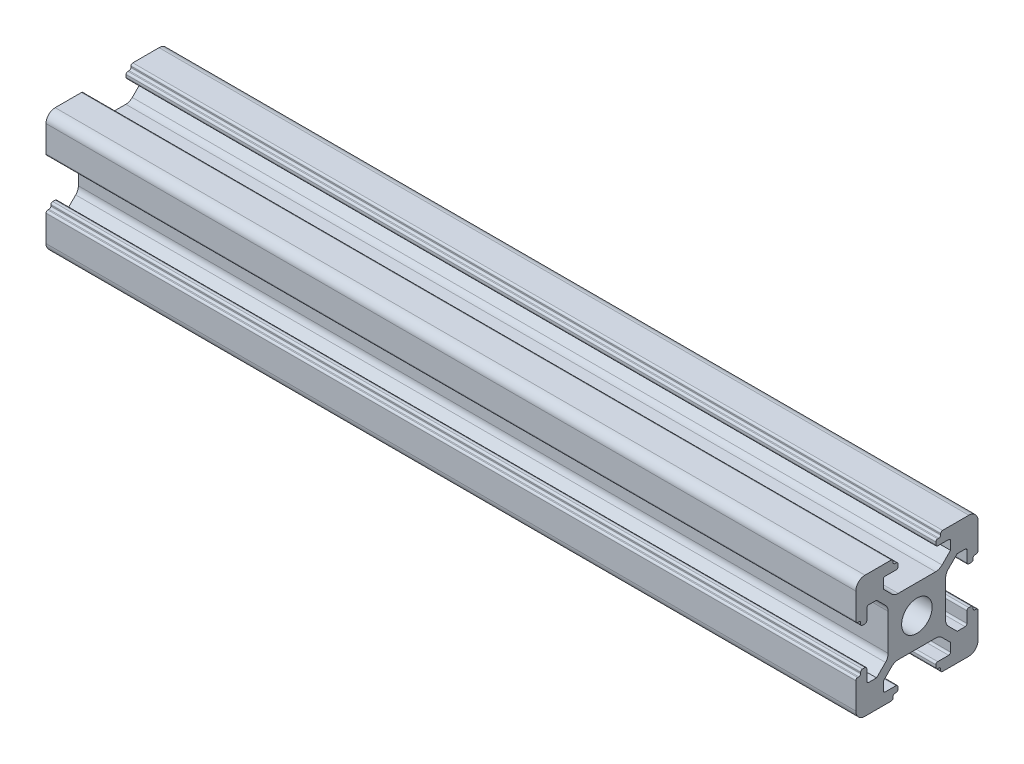
SolidWorks part; units mm, degrees
ref_plane "Front Plane" through (0, 0, 0) normal (0, 0, 1) x (1, 0, 0)
ref_plane "Top Plane" through (0, 0, 0) normal (0, 1, 0) x (1, 0, 0)
ref_plane "Right Plane" through (0, 0, 0) normal (1, 0, 0) x (0, 0, -1)
sketch "Sketch1" plane through (0, 0, 0) normal (1, 0, 0) x (0, 0, -1)
  line L0 (0, 0) -> (0, 50000) construction
  line L1 (0, 0) -> (-50000, 0) construction
  line L2 (10, 4.2) -> (10, 8.5)
  line L3 (9.7, 3.9) -> (9.5, 3.9)
  line L4 (9.2, 3.6) -> (9.2, 3.4)
  line L5 (8.9, 3.1) -> (8.5, 3.1)
  line L6 (8.2, 3.4) -> (8.2, 5.2)
  line L7 (7.9, 5.5) -> (6.6, 5.5)
  line L8 (6.6, 5.5) -> (5.1393, 4.0393)
  line L9 (8.5, 10) -> (4.2, 10)
  line L10 (3.9, 9.7) -> (3.9, 9.5)
  line L11 (3.6, 9.2) -> (3.4, 9.2)
  line L12 (3.1, 8.9) -> (3.1, 8.5)
  line L13 (3.4, 8.2) -> (5.2, 8.2)
  line L14 (5.5, 7.9) -> (5.5, 6.5213)
  line L15 (5.5, 6.5213) -> (4.118, 5.1393)
  line L16 (4.7, 2.9787) -> (4.7, -2.9787)
  line L17 (3.0574, 4.7) -> (-3.0574, 4.7)
  line L18 (-4.7, 2.9787) -> (-4.7, -2.9787)
  line L19 (-5.5, 6.5213) -> (-4.118, 5.1393)
  line L20 (-5.5, 7.9) -> (-5.5, 6.5213)
  line L21 (-3.4, 8.2) -> (-5.2, 8.2)
  line L22 (-3.1, 8.9) -> (-3.1, 8.5)
  line L23 (-3.6, 9.2) -> (-3.4, 9.2)
  line L24 (-3.9, 9.7) -> (-3.9, 9.5)
  line L25 (-8.5, 10) -> (-4.2, 10)
  line L26 (-6.6, 5.5) -> (-5.1393, 4.0393)
  line L27 (-7.9, 5.5) -> (-6.6, 5.5)
  line L28 (-8.2, 3.4) -> (-8.2, 5.2)
  line L29 (-8.9, 3.1) -> (-8.5, 3.1)
  line L30 (-9.2, 3.6) -> (-9.2, 3.4)
  line L31 (-9.7, 3.9) -> (-9.5, 3.9)
  line L32 (-10, 4.2) -> (-10, 8.5)
  line L33 (-10, -4.2) -> (-10, -8.5)
  line L34 (-9.7, -3.9) -> (-9.5, -3.9)
  line L35 (-9.2, -3.6) -> (-9.2, -3.4)
  line L36 (-8.9, -3.1) -> (-8.5, -3.1)
  line L37 (-8.2, -3.4) -> (-8.2, -5.2)
  line L38 (-7.9, -5.5) -> (-6.6, -5.5)
  line L39 (-6.6, -5.5) -> (-5.1393, -4.0393)
  line L40 (-8.5, -10) -> (-4.2, -10)
  line L41 (-3.9, -9.7) -> (-3.9, -9.5)
  line L42 (-3.6, -9.2) -> (-3.4, -9.2)
  line L43 (-3.1, -8.9) -> (-3.1, -8.5)
  line L44 (-3.4, -8.2) -> (-5.2, -8.2)
  line L45 (-5.5, -7.9) -> (-5.5, -6.5213)
  line L46 (-5.5, -6.5213) -> (-4.118, -5.1393)
  line L47 (3.0574, -4.7) -> (-3.0574, -4.7)
  line L48 (5.5, -6.5213) -> (4.118, -5.1393)
  line L49 (5.5, -7.9) -> (5.5, -6.5213)
  line L50 (3.4, -8.2) -> (5.2, -8.2)
  line L51 (3.1, -8.9) -> (3.1, -8.5)
  line L52 (3.6, -9.2) -> (3.4, -9.2)
  line L53 (3.9, -9.7) -> (3.9, -9.5)
  line L54 (8.5, -10) -> (4.2, -10)
  line L55 (6.6, -5.5) -> (5.1393, -4.0393)
  line L56 (7.9, -5.5) -> (6.6, -5.5)
  line L57 (8.2, -3.4) -> (8.2, -5.2)
  line L58 (8.9, -3.1) -> (8.5, -3.1)
  line L59 (9.2, -3.6) -> (9.2, -3.4)
  line L60 (9.7, -3.9) -> (9.5, -3.9)
  line L61 (10, -4.2) -> (10, -8.5)
  circle A0 centre (0, 0) radius 2.5
  arc A1 (10, 8.5) -> (8.5, 10) centre (8.5, 8.5) ccw
  arc A2 (9.7, 3.9) -> (10, 4.2) centre (9.7, 4.2) ccw
  arc A3 (9.5, 3.9) -> (9.2, 3.6) centre (9.5, 3.6) ccw
  arc A4 (9.2, 3.4) -> (8.9, 3.1) centre (8.9, 3.4) cw
  arc A5 (8.5, 3.1) -> (8.2, 3.4) centre (8.5, 3.4) cw
  arc A6 (8.2, 5.2) -> (7.9, 5.5) centre (7.9, 5.2) ccw
  arc A7 (5.2, 8.2) -> (5.5, 7.9) centre (5.2, 7.9) cw
  arc A8 (3.1, 8.5) -> (3.4, 8.2) centre (3.4, 8.5) ccw
  arc A9 (3.4, 9.2) -> (3.1, 8.9) centre (3.4, 8.9) ccw
  arc A10 (4.2, 10) -> (3.9, 9.7) centre (4.2, 9.7) ccw
  arc A11 (3.9, 9.5) -> (3.6, 9.2) centre (3.6, 9.5) cw
  arc A12 (4.7, 2.9787) -> (5.1393, 4.0393) centre (6.2, 2.9787) cw
  arc A13 (3.0574, 4.7) -> (4.118, 5.1393) centre (3.0574, 6.2) ccw
  arc A14 (-3.0574, 4.7) -> (-4.118, 5.1393) centre (-3.0574, 6.2) cw
  arc A15 (-4.7, 2.9787) -> (-5.1393, 4.0393) centre (-6.2, 2.9787) ccw
  arc A16 (-3.9, 9.5) -> (-3.6, 9.2) centre (-3.6, 9.5) ccw
  arc A17 (-4.2, 10) -> (-3.9, 9.7) centre (-4.2, 9.7) cw
  arc A18 (-3.4, 9.2) -> (-3.1, 8.9) centre (-3.4, 8.9) cw
  arc A19 (-3.1, 8.5) -> (-3.4, 8.2) centre (-3.4, 8.5) cw
  arc A20 (-5.2, 8.2) -> (-5.5, 7.9) centre (-5.2, 7.9) ccw
  arc A21 (-8.2, 5.2) -> (-7.9, 5.5) centre (-7.9, 5.2) cw
  arc A22 (-8.5, 3.1) -> (-8.2, 3.4) centre (-8.5, 3.4) ccw
  arc A23 (-9.2, 3.4) -> (-8.9, 3.1) centre (-8.9, 3.4) ccw
  arc A24 (-9.5, 3.9) -> (-9.2, 3.6) centre (-9.5, 3.6) cw
  arc A25 (-9.7, 3.9) -> (-10, 4.2) centre (-9.7, 4.2) cw
  arc A26 (-10, 8.5) -> (-8.5, 10) centre (-8.5, 8.5) cw
  arc A27 (-10, -8.5) -> (-8.5, -10) centre (-8.5, -8.5) ccw
  arc A28 (-9.7, -3.9) -> (-10, -4.2) centre (-9.7, -4.2) ccw
  arc A29 (-9.5, -3.9) -> (-9.2, -3.6) centre (-9.5, -3.6) ccw
  arc A30 (-9.2, -3.4) -> (-8.9, -3.1) centre (-8.9, -3.4) cw
  arc A31 (-8.5, -3.1) -> (-8.2, -3.4) centre (-8.5, -3.4) cw
  arc A32 (-8.2, -5.2) -> (-7.9, -5.5) centre (-7.9, -5.2) ccw
  arc A33 (-5.2, -8.2) -> (-5.5, -7.9) centre (-5.2, -7.9) cw
  arc A34 (-3.1, -8.5) -> (-3.4, -8.2) centre (-3.4, -8.5) ccw
  arc A35 (-3.4, -9.2) -> (-3.1, -8.9) centre (-3.4, -8.9) ccw
  arc A36 (-4.2, -10) -> (-3.9, -9.7) centre (-4.2, -9.7) ccw
  arc A37 (-3.9, -9.5) -> (-3.6, -9.2) centre (-3.6, -9.5) cw
  arc A38 (-4.7, -2.9787) -> (-5.1393, -4.0393) centre (-6.2, -2.9787) cw
  arc A39 (-3.0574, -4.7) -> (-4.118, -5.1393) centre (-3.0574, -6.2) ccw
  arc A40 (3.0574, -4.7) -> (4.118, -5.1393) centre (3.0574, -6.2) cw
  arc A41 (4.7, -2.9787) -> (5.1393, -4.0393) centre (6.2, -2.9787) ccw
  arc A42 (3.9, -9.5) -> (3.6, -9.2) centre (3.6, -9.5) ccw
  arc A43 (4.2, -10) -> (3.9, -9.7) centre (4.2, -9.7) cw
  arc A44 (3.4, -9.2) -> (3.1, -8.9) centre (3.4, -8.9) cw
  arc A45 (3.1, -8.5) -> (3.4, -8.2) centre (3.4, -8.5) cw
  arc A46 (5.2, -8.2) -> (5.5, -7.9) centre (5.2, -7.9) ccw
  arc A47 (8.2, -5.2) -> (7.9, -5.5) centre (7.9, -5.2) cw
  arc A48 (8.5, -3.1) -> (8.2, -3.4) centre (8.5, -3.4) ccw
  arc A49 (9.2, -3.4) -> (8.9, -3.1) centre (8.9, -3.4) ccw
  arc A50 (9.5, -3.9) -> (9.2, -3.6) centre (9.5, -3.6) cw
  arc A51 (9.7, -3.9) -> (10, -4.2) centre (9.7, -4.2) cw
  arc A52 (10, -8.5) -> (8.5, -10) centre (8.5, -8.5) cw
  point P24 (10, 10)
  point P41 (3.1, 9.2)
  point P44 (3.9, 10)
  point P94 (4.7, 0)
  point P95 (0, 4.7)
  point P175 (0, -4.7)
  point P176 (-4.7, 0)
  dimension "D1" = 5
  dimension "D15" = 1.5
  dimension "D16" = 0.3
  dimension "D19" = 1.5
  dimension "D2" = 20
  dimension "D3" = 1.8
  dimension "D4" = 6.2
  dimension "D5" = 3.4
  dimension "D6" = 11
  dimension "D7" = 6.1
  dimension "D8" = 1.5
  dimension "D9" = 20
  dimension "D10" = 6.1
  dimension "D11" = 6.2
  dimension "D12" = 11
  dimension "D13" = 45
  dimension "D14" = 1.8
  dimension "D17" = 3.5
  dimension "D18" = 3.5
extrude "Boss-Extrude2" add sketch "Sketch1" along normal mid plane 132.5
